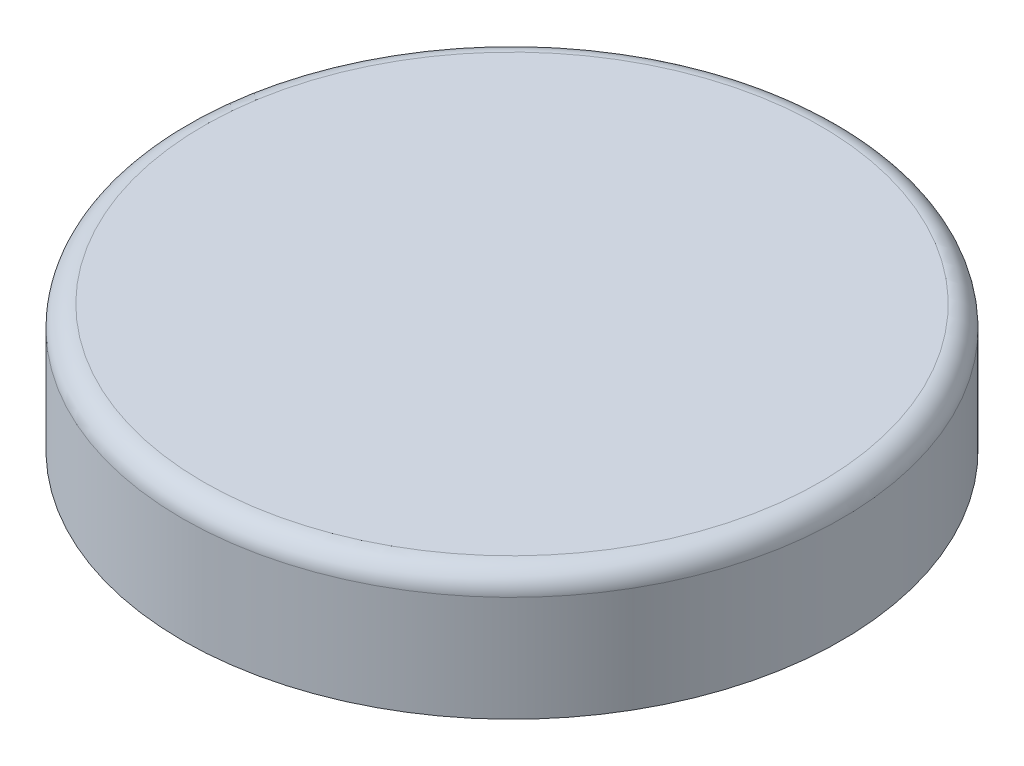
SolidWorks part; units mm, degrees
ref_plane "Front Plane" through (0, 0, 0) normal (0, 0, 1) x (1, 0, 0)
ref_plane "Top Plane" through (0, 0, 0) normal (0, 1, 0) x (1, 0, 0)
ref_plane "Right Plane" through (0, 0, 0) normal (1, 0, 0) x (0, 0, -1)
sketch "Sketch1" plane through (0, 0, 0) normal (0, 1, 0) x (1, 0, 0)
  circle A0 centre (0, 0) radius 78.0685
extrude "Boss-Extrude1" add sketch "Sketch1" along normal blind 30
fillet "Fillet1" radius 5 1 edges at (0, 30, 78.0685)
